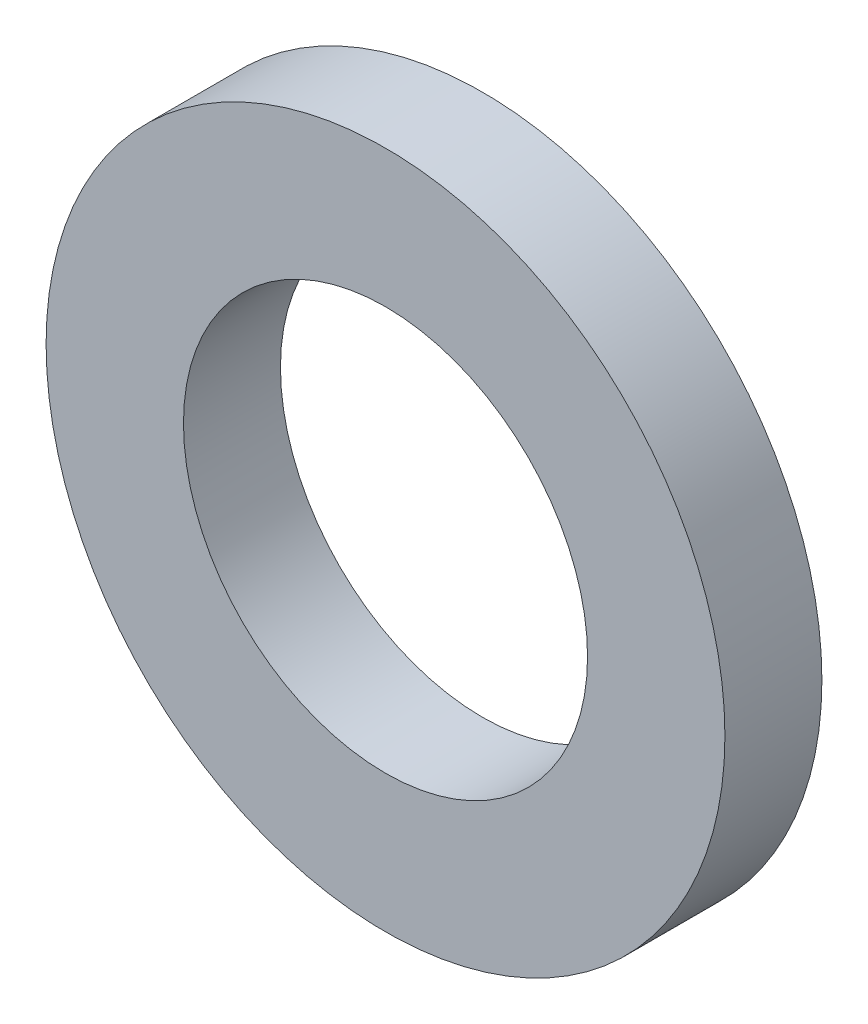
SolidWorks part; units mm, degrees
ref_plane "Front Plane" through (0, 0, 0) normal (0, 0, 1) x (1, 0, 0)
ref_plane "Top Plane" through (0, 0, 0) normal (0, 1, 0) x (1, 0, 0)
ref_plane "Right Plane" through (0, 0, 0) normal (1, 0, 0) x (0, 0, -1)
sketch "Sketch1" plane through (0, 0, 0) normal (0, 0, 1) x (1, 0, 0)
  circle A0 centre (0, 0) radius 21
  circle A1 centre (0, 0) radius 12.5
  dimension "D1" = 25
  dimension "D2" = 42
extrude "Boss-Extrude1" add sketch "Sketch1" along normal blind 6
